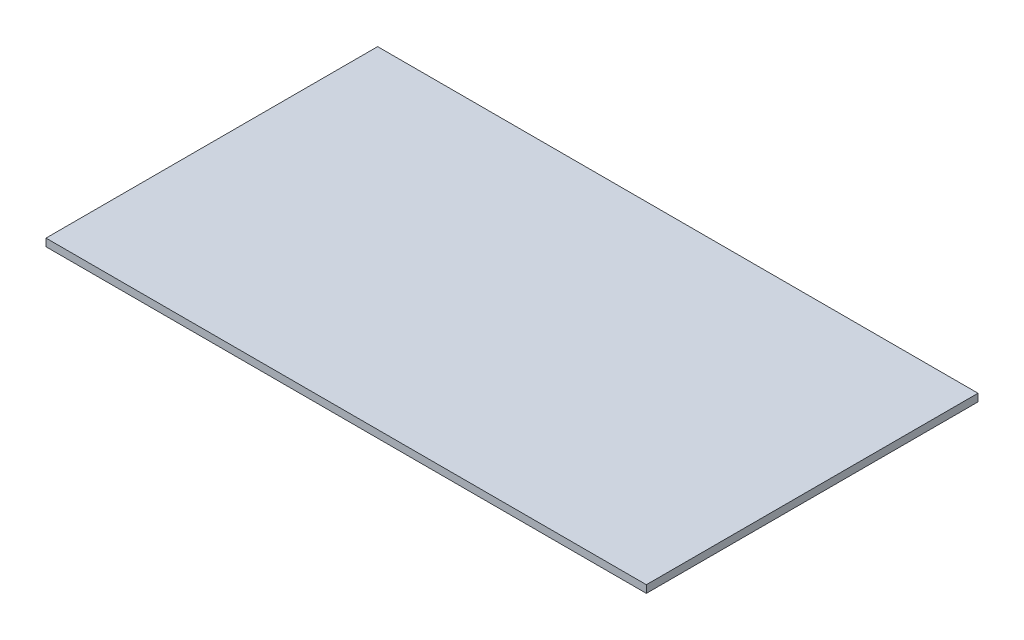
SolidWorks part; units mm, degrees
material "Polyethylene Cross-Linked"
ref_plane "Front Plane" through (0, 0, 0) normal (0, 0, 1) x (1, 0, 0)
ref_plane "Top Plane" through (0, 0, 0) normal (0, 1, 0) x (1, 0, 0)
ref_plane "Right Plane" through (0, 0, 0) normal (1, 0, 0) x (0, 0, -1)
sketch "Sketch1" plane through (0, 0, 0) normal (0, 1, 0) x (1, 0, 0)
  line L1 (0, 0) -> (252.9, 0)
  line L2 (0, 0) -> (0, 139.7)
  line L3 (0, 139.7) -> (252.9, 139.7)
  line L4 (252.9, 0) -> (252.9, 139.7)
  dimension "D1" = 139.7
  dimension "D2" = 252.9
extrude "Boss-Extrude1" add sketch "Sketch1" along normal blind 3.175
